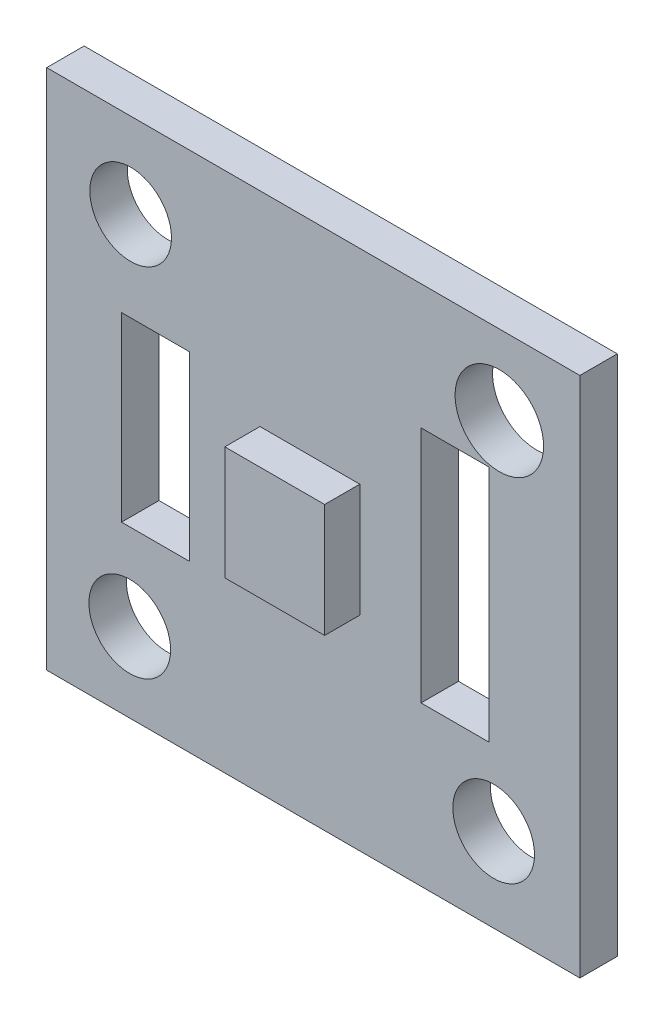
SolidWorks part; units mm, degrees
ref_plane "Front Plane" through (0, 0, 0) normal (0, 0, 1) x (1, 0, 0)
ref_plane "Top Plane" through (0, 0, 0) normal (0, 1, 0) x (1, 0, 0)
ref_plane "Right Plane" through (0, 0, 0) normal (1, 0, 0) x (0, 0, -1)
sketch "Sketch1" plane through (0, 0, 0) normal (0, 0, 1) x (1, 0, 0)
  line L1 (0, 0) -> (23.5, 0)
  line L2 (0, 0) -> (0, 23)
  line L3 (0, 23) -> (23.5, 23)
  line L4 (23.5, 0) -> (23.5, 23)
  dimension "D1" = 23.5
  dimension "D2" = 23
extrude "Boss-Extrude1" add sketch "Sketch1" along normal blind 1.65
sketch "Sketch2" plane through (0, 0, 1.65) normal (0, 0, 1) x (1, 0, 0)
  line L0 (0, 0) -> (23.5, 0) construction
  line L1 (9.4, 14) -> (13.8, 14)
  line L2 (9.4, 14) -> (9.4, 9)
  line L3 (9.4, 9) -> (13.8, 9)
  line L4 (13.8, 14) -> (13.8, 9)
  line L5 (0, 23) -> (0, 0) construction
  dimension "D1" = 5
  dimension "D2" = 4.4
  dimension "D3" = 14
  dimension "D4" = 13.8
extrude "Boss-Extrude2" add sketch "Sketch2" along normal blind 1.55
sketch "Sketch3" plane through (0, 0, 1.65) normal (0, 0, 1) x (1, 0, 0)
  line L0 (23.5, 23) -> (0, 23) construction
  line L1 (16.5, 17.5) -> (19.5, 17.5)
  line L2 (16.5, 17.5) -> (16.5, 7)
  line L3 (16.5, 7) -> (19.5, 7)
  line L4 (19.5, 17.5) -> (19.5, 7)
  line L5 (23.5, 0) -> (23.5, 23) construction
  dimension "D1" = 5.5
  dimension "D2" = 10.5
  dimension "D3" = 3
  dimension "D4" = 4
extrude "Cut-Extrude1" cut sketch "Sketch3" against normal up to next
sketch "Sketch4" plane through (0, 0, 1.65) normal (0, 0, 1) x (1, 0, 0)
  line L0 (23.5, 23) -> (0, 23) construction
  line L1 (3.3, 15.3) -> (6.3, 15.3)
  line L2 (3.3, 15.3) -> (3.3, 7.3)
  line L3 (3.3, 7.3) -> (6.3, 7.3)
  line L4 (6.3, 15.3) -> (6.3, 7.3)
  line L5 (0, 23) -> (0, 0) construction
  dimension "D1" = 3
  dimension "D2" = 8
  dimension "D3" = 7.7
  dimension "D4" = 3.3
extrude "Cut-Extrude2" cut sketch "Sketch4" against normal up to next
sketch "Sketch5" plane through (0, 0, 1.65) normal (0, 0, 1) x (1, 0, 0)
  line L0 (23.5, 23) -> (0, 23) construction
  line L1 (23.5, 0) -> (23.5, 23) construction
  line L2 (0, 0) -> (23.5, 0) construction
  line L3 (0, 23) -> (0, 0) construction
  circle A0 centre (3.7, 19.25) radius 1.8
  circle A1 centre (19.95, 19.5) radius 1.95
  circle A2 centre (19.7, 3.7) radius 1.8
  circle A3 centre (3.66, 3.5) radius 1.8
  dimension "D1" = 3.6
  dimension "D2" = 3.9
  dimension "D3" = 3.6
  dimension "D4" = 3.6
  dimension "D5" = 3.5
  dimension "D6" = 3.55
  dimension "D7" = 3.8
  dimension "D8" = 3.7
  dimension "D9" = 3.5
  dimension "D10" = 3.66
  dimension "D11" = 3.75
  dimension "D12" = 3.7
extrude "Cut-Extrude3" cut sketch "Sketch5" against normal up to next
